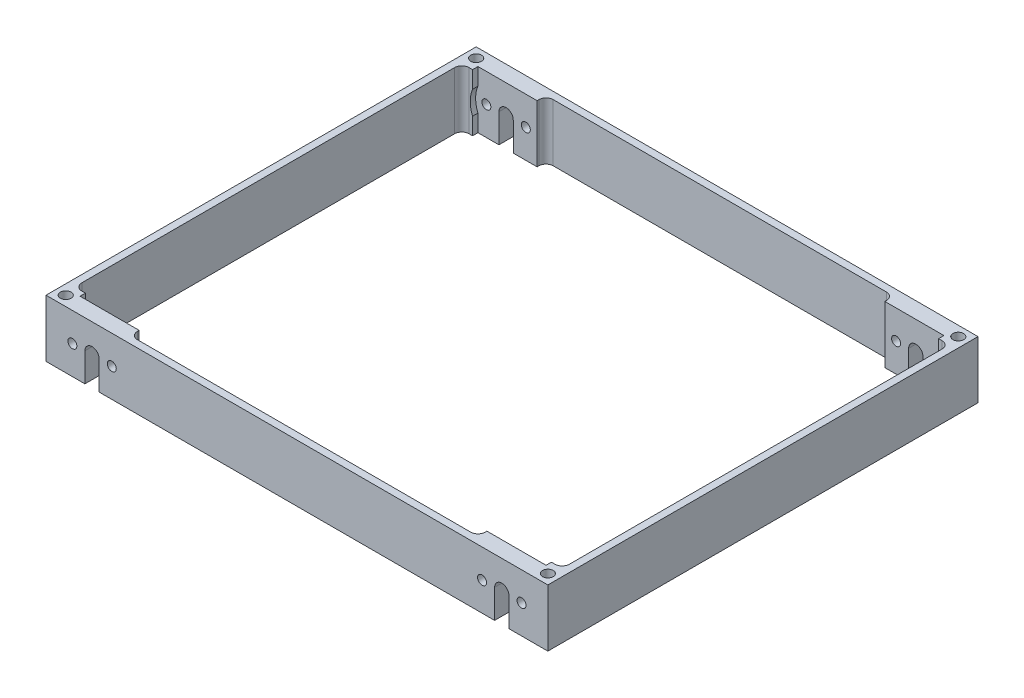
SolidWorks part; units mm, degrees
material "PET"
ref_plane "Front Plane" through (0, 0, 0) normal (0, 0, 1) x (1, 0, 0)
ref_plane "Top Plane" through (0, 0, 0) normal (0, 1, 0) x (1, 0, 0)
ref_plane "Right Plane" through (0, 0, 0) normal (1, 0, 0) x (0, 0, -1)
sketch "Sketch1" plane through (0, 0, 0) normal (0, 1, 0) x (1, 0, 0)
  line L0 (-135.5, 115.5) -> (-4.5, 115.5)
  line L1 (-140, 120) -> (0, 120)
  line L2 (-140, 120) -> (-140, 0)
  line L3 (-140, 0) -> (0, 0)
  line L4 (0, 120) -> (0, 0)
  line L5 (-4.5, 115.5) -> (-4.5, 4.5)
  line L6 (-135.5, 4.5) -> (-4.5, 4.5)
  line L7 (-135.5, 115.5) -> (-135.5, 4.5)
  dimension "D1" = 120
  dimension "D2" = 140
  dimension "D3" = 4.5
extrude "Boss-Extrude1" add sketch "Sketch1" along normal blind 16
sketch "Sketch3" plane through (0, 0, 0) normal (0, 0, 1) x (1, 0, 0)
  line L0 (-140, 8) -> (-129.15, 8) construction
  line L1 (-140, 16) -> (-140, 0) construction
  line L2 (0, 16) -> (0, 0) construction
  line L3 (-10.85, 8) -> (0, 8) construction
  line L4 (-127.15, 8) -> (-12.85, 8) construction
  line L5 (-129.15, 8) -> (-129.15, 0)
  line L6 (-140, 0) -> (0, 0) construction
  line L7 (-125.15, 8) -> (-125.15, 0)
  line L8 (-14.85, 8) -> (-14.85, 0)
  line L9 (-10.85, 8) -> (-10.85, 0)
  line L10 (-10.85, 0) -> (-14.85, 0)
  line L11 (-129.15, 0) -> (-125.15, 0)
  arc A0 (-125.15, 8) -> (-129.15, 8) centre (-127.15, 8) ccw
  arc A1 (-10.85, 8) -> (-14.85, 8) centre (-12.85, 8) ccw
  dimension "D1" = 4
  dimension "D2" = 114.3
extrude "Cut-Extrude1" cut sketch "Sketch3" against normal through all
sketch "Sketch5" plane through (0, 0, 0) normal (0, 0, 1) x (1, 0, 0)
  line L0 (-127.15, 8) -> (-132.65, 8) construction
  line L1 (-127.15, 8) -> (-121.65, 8) construction
  line L2 (-70, 16) -> (-70, 0) construction
  line L3 (-140, 16) -> (0, 16) construction
  line L4 (-125.15, 0) -> (-14.85, 0) construction
  circle A0 centre (-132.65, 8) radius 1.25
  circle A1 centre (-121.65, 8) radius 1.25
  circle A2 centre (-18.35, 8) radius 1.25
  circle A3 centre (-7.35, 8) radius 1.25
  dimension "D2" = 2.5
  dimension "D1" = 11
extrude "Cut-Extrude3" cut sketch "Sketch5" against normal through all
sketch "Sketch4" plane through (0, 16, 0) normal (0, 1, 0) x (1, 0, 0)
  line L1 (-138, 115.5) -> (-118.5, 115.5)
  line L2 (-138, 115.5) -> (-138, 4.5)
  line L3 (-138, 4.5) -> (-118.5, 4.5)
  line L4 (-2, 115.5) -> (-2, 4.5)
  line L5 (-135.5, 4.5) -> (-4.5, 4.5) construction
  line L6 (-4.5, 115.5) -> (-135.5, 115.5) construction
  line L7 (-140, 120) -> (-140, 0) construction
  line L8 (0, 0) -> (0, 120) construction
  line L9 (-118.5, 4.5) -> (-118.5, 2)
  line L10 (-118.5, 118) -> (-21.5, 118)
  line L11 (-118.5, 118) -> (-118.5, 115.5)
  line L12 (-118.5, 2) -> (-21.5, 2)
  line L13 (-21.5, 118) -> (-21.5, 115.5)
  line L14 (-21.5, 115.5) -> (-2, 115.5)
  line L15 (-21.5, 4.5) -> (-2, 4.5)
  line L16 (-21.5, 4.5) -> (-21.5, 2)
  line L19 (-70, 118) -> (-70, 2) construction
  dimension "D1" = 2
  dimension "D2" = 2
  dimension "D3" = 2.5
  dimension "D4" = 19.5
extrude "Cut-Extrude2" cut sketch "Sketch4" against normal through all
sketch "Sketch6" plane through (0, 0, 0) normal (0, 0, 1) x (1, 0, 0)
  line L0 (-138, 16) -> (-138, 0) construction
  line L1 (-140, 16) -> (0, 16) construction
  line L2 (-140, 0) -> (-129.15, 0) construction
  line L3 (-140, 16) -> (-140, 0) construction
  line L7 (-140, 16) -> (-135, 16)
  line L8 (-140, 8) -> (0, 8) construction
  line L9 (0, 16) -> (0, 0) construction
  line L10 (-70, 16) -> (-70, 0) construction
  line L11 (-125.15, 0) -> (-14.85, 0) construction
  line L24 (-140, 16) -> (-140, 0)
  line L25 (-135, 16) -> (-135, 11.26)
  line L26 (-135, 0) -> (-140, 0)
  line L27 (-5, 16) -> (-5, 11.26)
  line L28 (0, 16) -> (-5, 16)
  line L29 (0, 16) -> (0, 0)
  line L30 (-5, 0) -> (0, 0)
  line L31 (-135, 4.74) -> (-135, 0)
  line L32 (-5, 4.74) -> (-5, 0)
  arc A1 (-135, 11.26) -> (-135, 4.74) centre (-127.15, 8) ccw
  arc A2 (-5, 11.26) -> (-5, 4.74) centre (-12.85, 8) cw
  dimension "D1" = 2
  dimension "D2" = 5
extrude "Boss-Extrude2" add sketch "Sketch6" against normal up to surface (115.5 mm away) up to face at (-127.7, 6.25, -115.5)
sketch "Sketch7" plane through (0, 16, 0) normal (0, 1, 0) x (1, 0, 0)
  line L0 (-140, 120) -> (-140, 0) construction
  line L1 (-138, 114) -> (-2, 114)
  line L2 (-138, 114) -> (-138, 6)
  line L3 (-138, 6) -> (-2, 6)
  line L4 (-2, 114) -> (-2, 6)
  line L5 (0, 0) -> (0, 120) construction
  line L6 (0, 120) -> (-140, 120) construction
  line L7 (-140, 0) -> (0, 0) construction
  dimension "D1" = 2
  dimension "D2" = 2
  dimension "D3" = 6
  dimension "D4" = 6
extrude "Cut-Extrude4" cut sketch "Sketch7" against normal through all contours L2 L1 L4 L3
fillet "Fillet1" radius 2 8 edges at (-21.5, 8, -2) (-118.5, 8, -2) (-21.5, 8, -118) (-118.5, 8, -118) (-2, 8, -6) (-138, 8, -6) (-2, 8, -114) (-138, 8, -114)
ref_plane "Plane1" through (-118.5, 16, -4.5) normal (1, 0, 0) x (0, 0, -1)
sketch "Sketch9" plane through (0, 0, 0) normal (0, 1, 0) x (1, 0, 0)
  line L0 (-70, 120) -> (-70, 0) construction
  line L1 (0, 120) -> (-140, 120) construction
  line L2 (-140, 0) -> (0, 0) construction
  line L4 (-140, 120) -> (-140, 0) construction
  line L5 (-140, 60) -> (0, 60) construction
  line L6 (0, 0) -> (0, 120) construction
  circle A0 centre (-137.25, 2.75) radius 1.3
  circle A1 centre (-2.75, 2.75) radius 1.3
  circle A2 centre (-2.75, 117.25) radius 1.3
  circle A3 centre (-137.25, 117.25) radius 1.3
  dimension "D1" = 2.75
  dimension "D2" = 2.6
  dimension "D3" = 2.75
extrude "Cut-Extrude5" cut sketch "Sketch9" along normal blind 4
sketch "Sketch10" plane through (0, 16, 0) normal (0, 1, 0) x (1, 0, 0)
  line L0 (-70, 120) -> (-70, 0) construction
  line L1 (0, 120) -> (-140, 120) construction
  line L2 (-140, 0) -> (0, 0) construction
  line L3 (-137.25, 117.25) -> (-137.25, 120) construction
  line L4 (-140, 120) -> (-140, 0) construction
  line L5 (-140, 60) -> (0, 60) construction
  line L6 (0, 0) -> (0, 120) construction
  line L7 (-137.25, 117.25) -> (-140, 117.25) construction
  circle A0 centre (-137.25, 117.25) radius 1.5
  circle A1 centre (-2.75, 117.25) radius 1.5
  circle A2 centre (-2.75, 2.75) radius 1.5
  circle A3 centre (-137.25, 2.75) radius 1.5
  dimension "D1" = 3
  dimension "D2" = 2.75
extrude "Cut-Extrude6" cut sketch "Sketch10" against normal through all
